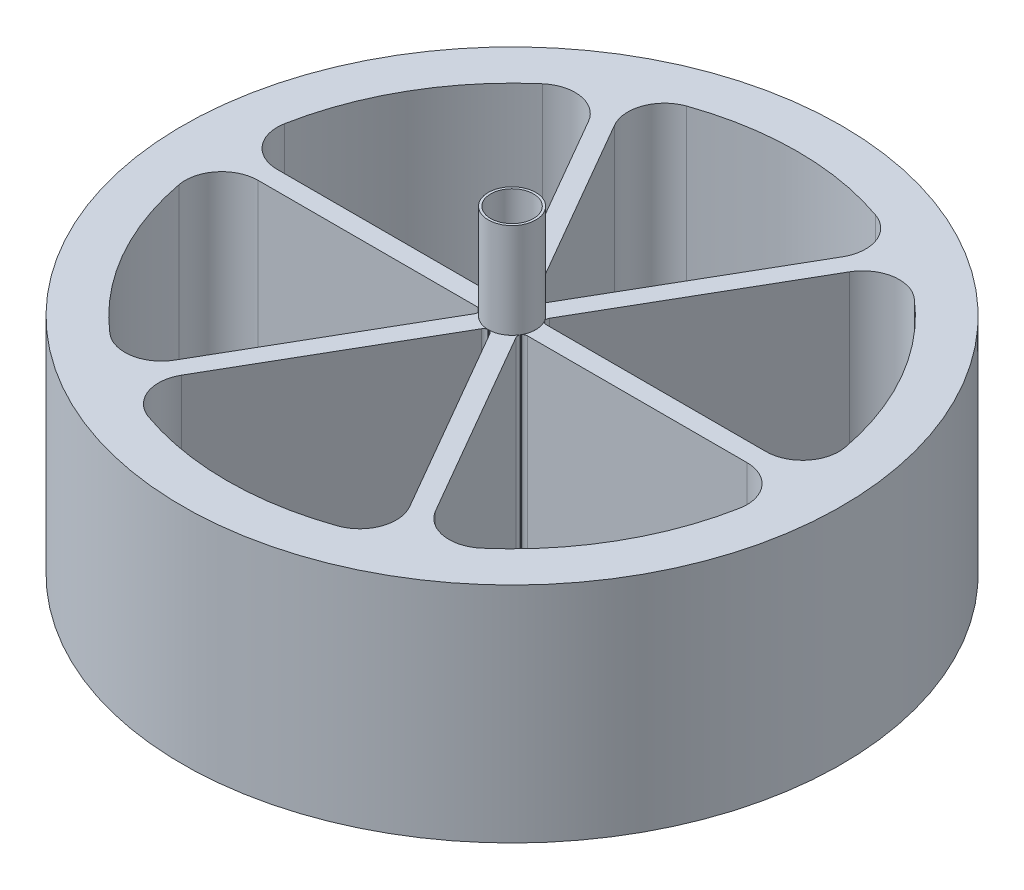
SolidWorks part; units mm, degrees
ref_plane "Front Plane" through (0, 0, 0) normal (0, 0, 1) x (1, 0, 0)
ref_plane "Top Plane" through (0, 0, 0) normal (0, 1, 0) x (1, 0, 0)
ref_plane "Right Plane" through (0, 0, 0) normal (1, 0, 0) x (0, 0, -1)
sketch "Sketch1" plane through (0, 0, 0) normal (0, 1, 0) x (1, 0, 0)
  circle A0 centre (0, 0) radius 1.5
  circle A1 centre (0, 0) radius 2.5
  dimension "D1" = 3
  dimension "D2" = 5
extrude "Boss-Extrude1" add sketch "Sketch1" along normal blind 10
sketch "Sketch2" plane through (0, 0, 0) normal (0, -1, 0) x (-1, 0, 0)
  line L1 (2.614, 1) -> (25.708, 1)
  line L2 (20.4475, 0) -> (20.4475, 1)
  line L3 (2.614, -1) -> (25.708, -1)
  line L4 (0.4409, -2.7637) -> (11.988, -22.7638)
  line L5 (2.173, -1.7637) -> (13.72, -21.7638)
  line L6 (-2.173, -1.7637) -> (-13.72, -21.7638)
  line L7 (-0.4409, -2.7637) -> (-11.988, -22.7638)
  line L8 (-2.614, 1) -> (-25.708, 1)
  line L9 (-2.614, -1) -> (-25.708, -1)
  line L10 (-0.4409, 2.7637) -> (-11.988, 22.7638)
  line L11 (-2.173, 1.7637) -> (-13.72, 21.7638)
  line L12 (2.173, 1.7637) -> (13.72, 21.7638)
  line L13 (0.4409, 2.7637) -> (11.988, 22.7638)
  line L14 (0.0941, -2.5116) -> (0.0272, -2.4999)
  line L15 (-0.0941, -2.5116) -> (-0.052, -2.4995)
  line L16 (2.2222, -1.1743) -> (2.1785, -1.2264)
  line L17 (2.128, -1.3373) -> (2.1386, -1.2947)
  line L18 (2.128, 1.3373) -> (2.1514, 1.2734)
  line L19 (2.2222, 1.1743) -> (2.1906, 1.2047)
  line L20 (-0.0941, 2.5116) -> (-0.0272, 2.4999)
  line L21 (0.0941, 2.5116) -> (0.052, 2.4995)
  line L22 (-2.2222, 1.1743) -> (-2.1785, 1.2264)
  line L23 (-2.128, 1.3373) -> (-2.1386, 1.2947)
  line L24 (-2.128, -1.3373) -> (-2.1514, -1.2734)
  line L25 (-2.2222, -1.1743) -> (-2.1906, -1.2047)
  arc A0 (9.9338, -28.3076) -> (19.5482, -22.7567) centre (0, 0) ccw
  arc A1 (25.708, 1) -> (29.482, 5.5509) centre (25.708, 4.8403) ccw
  circle A2 centre (0, 0) radius 2.5 construction
  arc A3 (2.2222, 1.1743) -> (2.614, 1) centre (2.614, 1.5276) ccw
  arc A4 (0.0272, -2.4999) -> (2.1386, -1.2947) centre (0, 0) ccw
  arc A5 (2.2222, -1.1743) -> (2.614, -1) centre (2.614, -1.5276) cw
  arc A6 (25.708, -1) -> (29.482, -5.5509) centre (25.708, -4.8403) cw
  arc A7 (2.128, -1.3373) -> (2.173, -1.7637) centre (2.6299, -1.5) ccw
  arc A8 (0.0941, -2.5116) -> (0.4409, -2.7637) centre (-0.0159, -3.0275) cw
  arc A9 (11.988, -22.7638) -> (9.9338, -28.3076) centre (8.6621, -24.6839) cw
  arc A10 (13.72, -21.7638) -> (19.5482, -22.7567) centre (17.0458, -19.8436) ccw
  arc A11 (-0.0941, -2.5116) -> (-0.4409, -2.7637) centre (0.0159, -3.0275) ccw
  arc A12 (-2.128, -1.3373) -> (-2.173, -1.7637) centre (-2.6299, -1.5) cw
  arc A13 (-13.72, -21.7638) -> (-19.5482, -22.7567) centre (-17.0458, -19.8436) cw
  arc A14 (-11.988, -22.7638) -> (-9.9338, -28.3076) centre (-8.6621, -24.6839) ccw
  arc A15 (-2.2222, -1.1743) -> (-2.614, -1) centre (-2.614, -1.5276) ccw
  arc A16 (-2.2222, 1.1743) -> (-2.614, 1) centre (-2.614, 1.5276) cw
  arc A17 (-25.708, 1) -> (-29.482, 5.5509) centre (-25.708, 4.8403) cw
  arc A18 (-25.708, -1) -> (-29.482, -5.5509) centre (-25.708, -4.8403) ccw
  arc A19 (-2.128, 1.3373) -> (-2.173, 1.7637) centre (-2.6299, 1.5) ccw
  arc A20 (-0.0941, 2.5116) -> (-0.4409, 2.7637) centre (0.0159, 3.0275) cw
  arc A21 (-11.988, 22.7638) -> (-9.9338, 28.3076) centre (-8.6621, 24.6839) cw
  arc A22 (-13.72, 21.7638) -> (-19.5482, 22.7567) centre (-17.0458, 19.8436) ccw
  arc A23 (0.0941, 2.5116) -> (0.4409, 2.7637) centre (-0.0159, 3.0275) ccw
  arc A24 (2.128, 1.3373) -> (2.173, 1.7637) centre (2.6299, 1.5) cw
  arc A25 (13.72, 21.7638) -> (19.5482, 22.7567) centre (17.0458, 19.8436) cw
  arc A26 (11.988, 22.7638) -> (9.9338, 28.3076) centre (8.6621, 24.6839) ccw
  arc A27 (-19.5482, -22.7567) -> (-9.9338, -28.3076) centre (0, 0) ccw
  arc A28 (-29.482, 5.5509) -> (-29.482, -5.5509) centre (0, 0) ccw
  arc A29 (-9.9338, 28.3076) -> (-19.5482, 22.7567) centre (0, 0) ccw
  arc A30 (19.5482, 22.7567) -> (9.9338, 28.3076) centre (0, 0) ccw
  arc A31 (29.482, -5.5509) -> (29.482, 5.5509) centre (0, 0) ccw
  arc A32 (-2.1514, -1.2734) -> (-0.052, -2.4995) centre (0, 0) ccw
  arc A33 (-2.1785, 1.2264) -> (-2.1906, -1.2047) centre (0, 0) ccw
  arc A34 (-0.0272, 2.4999) -> (-2.1386, 1.2947) centre (0, 0) ccw
  arc A35 (2.1514, 1.2734) -> (0.052, 2.4995) centre (0, 0) ccw
  arc A36 (2.1785, -1.2264) -> (2.1906, 1.2047) centre (0, 0) ccw
  point P85 (0, 0)
  point P108 (0, 0)
  dimension "D1" = 60
  dimension "D4" = 6
extrude "Boss-Extrude3" add sketch "Sketch2" along normal blind 23.5 separate body contours L6 A13 A27 A14 L7 A11 L15 A32 L24 A12 | L4 A9 A0 A10 L5 A7 L17 A4 L14 A8 | L1 A1 A31 A6 L3 A5 L16 A36 L19 A3 | L13 A26 A30 A25 L12 A24 L18 A35 L21 A23 | L11 A22 A29 A21 L10 A20 L20 A34 L23 A19 | L9 A18 A28 A17 L8 A16 L22 A33 L25 A15
sketch "Sketch5" plane through (0, -23.5, 0) normal (0, -1, 0) x (-1, 0, 0)
  circle A0 centre (0, 0) radius 30
  circle A1 centre (0, 0) radius 34.6666
extrude "Boss-Extrude4" add sketch "Sketch5" against normal blind 23.5
sketch "Sketch6" plane through (0, 10, 0) normal (0, 1, 0) x (1, 0, 0)
  circle A0 centre (0, 0) radius 1.5
extrude "Boss-Extrude5" add sketch "Sketch6" against normal blind 28
sketch "Sketch7" plane through (0, 10, 0) normal (0, 1, 0) x (1, 0, 0)
  circle A0 centre (0, 0) radius 2.25
  dimension "D1" = 4.5
extrude "Cut-Extrude1" cut sketch "Sketch7" against normal blind 28
